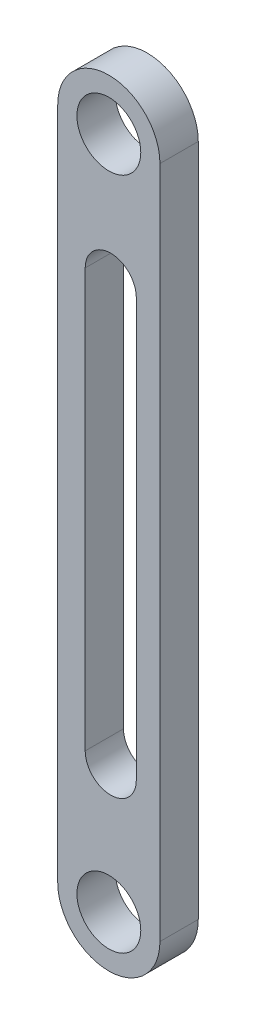
SolidWorks part; units mm, degrees
ref_plane "Front Plane" through (0, 0, 0) normal (1, 0, 0) x (0, 1, 0)
ref_plane "Top Plane" through (0, 0, 0) normal (0, 0, 1) x (0, 1, 0)
ref_plane "Right Plane" through (0, 0, 0) normal (0, 1, 0) x (-1, 0, 0)
sketch "Sketch1" plane through (0, 0, 0) normal (0, 0, 1) x (0, 1, 0)
  line L0 (-16.5294, 4.7941) -> (36.2106, 4.7941)
  line L1 (36.2106, -3.2059) -> (-16.5294, -3.2059)
  arc A0 (36.2106, 4.7941) -> (36.2106, -3.2059) centre (36.2106, 0.7941) cw
  arc A1 (-16.5294, -3.2059) -> (-16.5294, 4.7941) centre (-16.5294, 0.7941) cw
  dimension "D2" = 4
  dimension "D1" = 52.74
extrude "Boss-Extrude1" add sketch "Sketch1" along normal blind 3
sketch "Sketch2" plane through (0, 0, 3) normal (0, 0, 1) x (1, 0, 0)
  line L0 (-4.7941, 9.8406) -> (3.2059, 9.8406) construction
  line L1 (-4.7941, 36.2106) -> (-4.7941, -16.5294) construction
  line L2 (3.2059, -16.5294) -> (3.2059, 36.2106) construction
  circle A0 centre (-0.7941, -16.5294) radius 2.5
  circle A1 centre (-0.7941, 36.2106) radius 2.5
  dimension "D1" = 5
extrude "Cut-Extrude1" cut sketch "Sketch2" against normal up to next
sketch "Sketch3" plane through (0, 0, 3) normal (0, 0, 1) x (1, 0, 0)
  line L0 (-2.6455, -6.5294) -> (-2.6455, 26.2106)
  line L1 (1.3545, 26.2106) -> (1.3545, -6.5294)
  arc A0 (-2.6455, 26.2106) -> (1.3545, 26.2106) centre (-0.6455, 26.2106) cw
  arc A1 (1.3545, -6.5294) -> (-2.6455, -6.5294) centre (-0.6455, -6.5294) cw
  circle A2 centre (-0.7941, 36.2106) radius 2.5 construction
  circle A3 centre (-0.7941, -16.5294) radius 2.5 construction
  dimension "D1" = 2
  dimension "D2" = 10
  dimension "D3" = 10
extrude "Cut-Extrude2" cut sketch "Sketch3" against normal up to next
